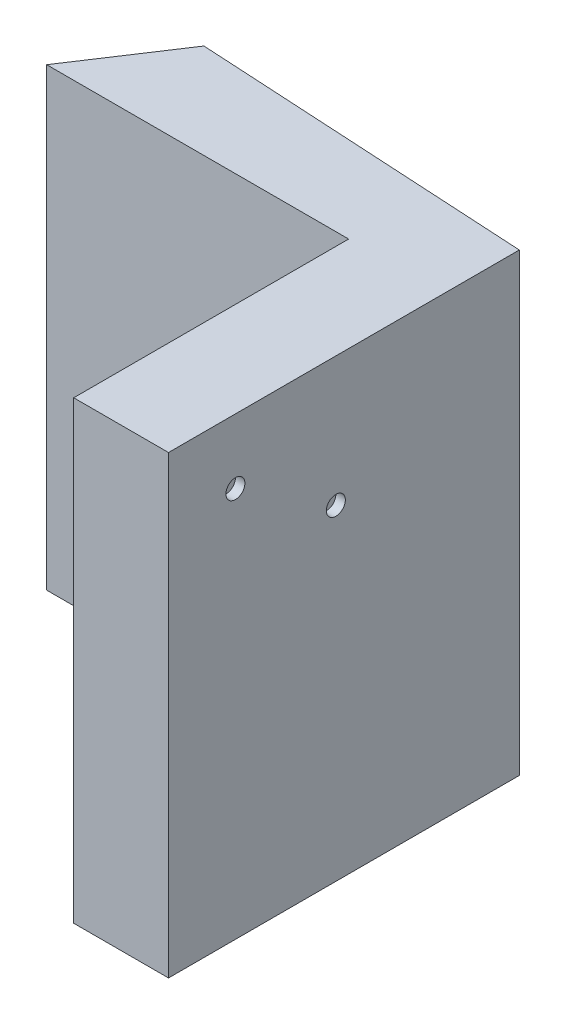
SolidWorks part; units mm, degrees
ref_plane "Front" through (0, 0, 0) normal (0, 0, 1) x (1, 0, 0)
ref_plane "Top" through (0, 0, 0) normal (0, 1, 0) x (1, 0, 0)
ref_plane "Right" through (0, 0, 0) normal (1, 0, 0) x (0, 0, -1)
sketch "Sketch1" plane through (0, 0, 0) normal (0, 1, 0) x (1, 0, 0)
  line L2 (0, 0) -> (0, -29)
  line L3 (0, -29) -> (10, -29)
  line L4 (10, 0) -> (10, -29)
  line L5 (10, 0) -> (-31.85, 0)
  line L6 (10, 0) -> (10, 10)
  line L7 (10, 10) -> (-31.85, 10)
  line L8 (-31.85, 0) -> (-31.85, 10)
  dimension "D1" = 41.85
  dimension "D2" = 29
  dimension "D3" = 10
  dimension "D4" = 10
extrude "Boss-Extrude1" add sketch "Sketch1" along normal blind 48 contours L8 L5 L6 L7 | L4 L5 L2 L3
sketch "Sketch3" plane through (0, 48, 0) normal (0, 1, 0) x (1, 0, 0)
  line L0 (-31.85, 10) -> (-25.2632, 10)
  line L1 (10, 10) -> (-31.85, 10) construction
  line L2 (-25.2632, 10) -> (-31.85, 0)
  line L3 (-31.85, 0) -> (-31.85, 10)
  dimension "D1" = 33.372
extrude "Cut-Extrude1" cut sketch "Sketch3" against normal blind 48
sketch "Sketch4" plane through (0, 0, 0) normal (0, 0, 1) x (1, 0, 0)
  circle A0 centre (-5.5896, 40.9808) radius 2
  circle A1 centre (-5.6297, 24.9791) radius 2
  circle A2 centre (-21.5913, 41.0209) radius 2
  circle A3 centre (-21.6315, 25.0192) radius 2
  circle A4 centre (-13.6297, 32.9791) radius 4.2
extrude "Cut-Extrude2" cut sketch "Sketch4" against normal blind 48
sketch "Sketch5" plane through (0, 48, 0) normal (0, 1, 0) x (1, 0, 0)
  line L0 (-25.2632, 10) -> (10, 8)
  line L1 (10, -29) -> (10, 10) construction
  line L2 (10, 8) -> (10, 10)
  line L3 (10, 10) -> (-25.2632, 10)
extrude "Cut-Extrude3" cut sketch "Sketch5" against normal blind 48
sketch "Sketch6" plane through (10, 0, 0) normal (1, 0, 0) x (0, 0, -1)
  line L0 (-29, 48) -> (-29, 0) construction
  line L1 (-29, 48) -> (-29, 0) construction
  line L2 (-29, 0) -> (8, 0) construction
  circle A0 centre (-21, 6.3919) radius 1
  circle A1 centre (-11, 15) radius 1
  dimension "D1" = 8
  dimension "D2" = 18
  dimension "D3" = 15
extrude "Cut-Extrude4" cut sketch "Sketch6" against normal blind 2
sketch "Sketch7" plane through (0.4843, 0, -8.5397) normal (0.0566, 0, -0.9984) x (-0.9984, 0, -0.0566)
  line L1 (25.7889, 0) -> (-9.531, 0) construction
  line L2 (-9.531, 0) -> (-9.531, 48) construction
  circle A0 centre (10.469, 7) radius 1
  dimension "D1" = 7
  dimension "D2" = 20
extrude "Cut-Extrude5" cut sketch "Sketch7" against normal blind 1
sketch "Sketch8" plane through (0, 0, 0) normal (0, -1, 0) x (1, 0, 0)
  line L1 (20.3, 60.2257) -> (-45.5651, 60.2257)
  line L2 (20.3, 60.2257) -> (20.3, -48.5087)
  line L3 (20.3, -48.5087) -> (-45.5651, -48.5087)
  line L4 (-45.5651, 60.2257) -> (-45.5651, -48.5087)
extrude "Cut-Extrude6" cut sketch "Sketch8" against normal blind 17.96
sketch "Sketch9" plane through (0, 48, 0) normal (0, 1, 0) x (1, 0, 0)
  line L0 (10, -29) -> (0, -29)
  line L1 (0, -29) -> (0, 0)
  line L2 (0, 0) -> (-31.85, 0)
  line L3 (-31.85, 0) -> (-25.2632, 10)
  line L4 (-25.2632, 10) -> (10, 8)
  line L5 (10, 8) -> (10, -29)
extrude "Boss-Extrude2" add sketch "Sketch9" along normal blind 17.96
sketch "Sketch10" plane through (10, 0, 0) normal (1, 0, 0) x (0, 0, -1)
  circle A0 centre (-21.9429, 59.1328) radius 1
  circle A1 centre (-11.3476, 52.3122) radius 1
extrude "Cut-Extrude7" cut sketch "Sketch10" against normal blind 1
sketch "Sketch11" plane through (0.4843, 0, -8.5397) normal (0.0566, 0, -0.9984) x (-0.9984, 0, -0.0566)
  circle A0 centre (1.7335, 58.3499) radius 1
extrude "Cut-Extrude8" cut sketch "Sketch11" against normal blind 1
